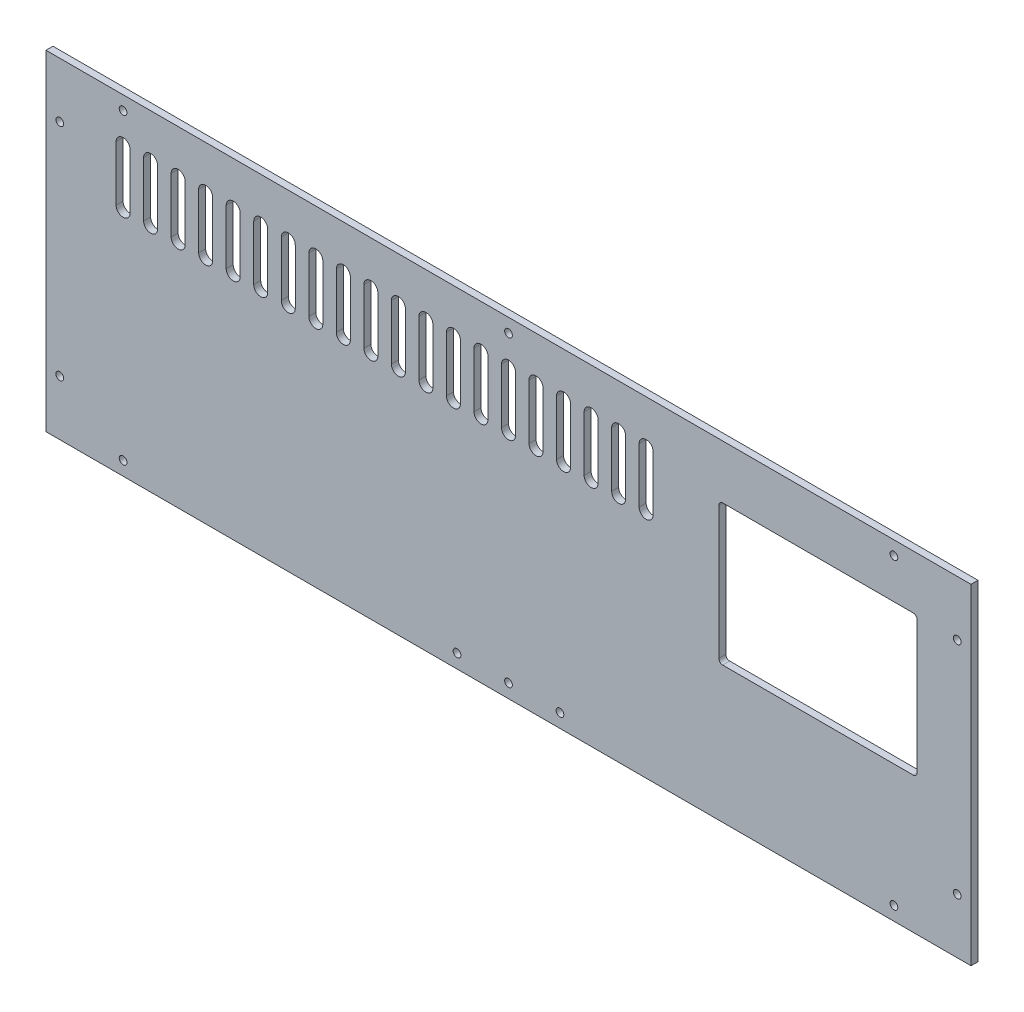
SolidWorks part; units mm, degrees
material "Acrylic (Medium-high impact)"
ref_plane "Front Plane" through (0, 0, 0) normal (0, 0, 1) x (1, 0, 0)
ref_plane "Top Plane" through (0, 0, 0) normal (0, 1, 0) x (1, 0, 0)
ref_plane "Right Plane" through (0, 0, 0) normal (1, 0, 0) x (0, 0, -1)
sketch "Sketch2" plane through (0, 0, 0) normal (0, 0, 1) x (1, 0, 0)
  line L1 (0, 0) -> (840, 0)
  line L2 (0, 0) -> (0, 300)
  line L3 (0, 300) -> (840, 300)
  line L4 (840, 0) -> (840, 300)
  dimension "D1" = 300
  dimension "D2" = 840
extrude "Boss-Extrude1" add sketch "Sketch2" along normal blind 6.35
sketch "Sketch3" plane through (0, 0, 6.35) normal (0, 0, 1) x (1, 0, 0)
  line L0 (420, 300) -> (420, 235) construction
  line L1 (840, 300) -> (0, 300) construction
  line L2 (420, 210) -> (420, 260) construction
  line L3 (413.65, 210) -> (413.65, 260)
  line L4 (426.35, 210) -> (426.35, 260)
  line L13 (451.35, 210) -> (451.35, 260)
  line L22 (438.65, 210) -> (438.65, 260)
  line L31 (445, 210) -> (445, 260) construction
  line L40 (476.35, 210) -> (476.35, 260)
  line L43 (463.65, 210) -> (463.65, 260)
  line L46 (470, 210) -> (470, 260) construction
  line L49 (501.35, 210) -> (501.35, 260)
  line L50 (488.65, 210) -> (488.65, 260)
  line L51 (401.35, 210) -> (401.35, 260)
  line L52 (388.65, 210) -> (388.65, 260)
  line L53 (395, 210) -> (395, 260) construction
  line L54 (376.35, 210) -> (376.35, 260)
  line L55 (363.65, 210) -> (363.65, 260)
  line L56 (370, 210) -> (370, 260) construction
  line L57 (351.35, 210) -> (351.35, 260)
  line L58 (338.65, 210) -> (338.65, 260)
  line L59 (345, 210) -> (345, 260) construction
  line L60 (326.35, 210) -> (326.35, 260)
  line L61 (313.65, 210) -> (313.65, 260)
  line L62 (320, 210) -> (320, 260) construction
  line L63 (301.35, 210) -> (301.35, 260)
  line L64 (288.65, 210) -> (288.65, 260)
  line L65 (295, 210) -> (295, 260) construction
  line L66 (276.35, 210) -> (276.35, 260)
  line L67 (263.65, 210) -> (263.65, 260)
  line L68 (270, 210) -> (270, 260) construction
  line L69 (251.35, 210) -> (251.35, 260)
  line L70 (238.65, 210) -> (238.65, 260)
  line L71 (245, 210) -> (245, 260) construction
  line L72 (226.35, 210) -> (226.35, 260)
  line L73 (213.65, 210) -> (213.65, 260)
  line L74 (220, 210) -> (220, 260) construction
  line L75 (201.35, 210) -> (201.35, 260)
  line L76 (188.65, 210) -> (188.65, 260)
  line L77 (195, 210) -> (195, 260) construction
  line L78 (176.35, 210) -> (176.35, 260)
  line L79 (163.65, 210) -> (163.65, 260)
  line L80 (170, 210) -> (170, 260) construction
  line L81 (151.35, 210) -> (151.35, 260)
  line L82 (138.65, 210) -> (138.65, 260)
  line L83 (145, 210) -> (145, 260) construction
  line L84 (126.35, 210) -> (126.35, 260)
  line L85 (113.65, 210) -> (113.65, 260)
  line L86 (120, 210) -> (120, 260) construction
  line L87 (101.35, 210) -> (101.35, 260)
  line L88 (88.65, 210) -> (88.65, 260)
  line L89 (95, 210) -> (95, 260) construction
  line L90 (76.35, 210) -> (76.35, 260)
  line L91 (63.65, 210) -> (63.65, 260)
  line L92 (70, 210) -> (70, 260) construction
  line L96 (426.35, 210) -> (401.35, 210) construction
  line L97 (495, 210) -> (495, 260) construction
  line L98 (526.35, 210) -> (526.35, 260)
  line L99 (513.65, 210) -> (513.65, 260)
  line L100 (520, 210) -> (520, 260) construction
  line L101 (551.35, 210) -> (551.35, 260)
  line L102 (538.65, 210) -> (538.65, 260)
  line L103 (545, 210) -> (545, 260) construction
  line L107 (426.35, 210) -> (451.35, 210) construction
  line L108 (38.65, 210) -> (38.65, 260) [skipped]
  line L109 (51.35, 210) -> (51.35, 260) [skipped]
  line L110 (563.65, 210) -> (563.65, 260) [skipped]
  line L111 (576.35, 210) -> (576.35, 260) [skipped]
  arc A0 (413.65, 210) -> (426.35, 210) centre (420, 210) ccw
  arc A1 (426.35, 260) -> (413.65, 260) centre (420, 260) ccw
  arc A32 (388.65, 210) -> (401.35, 210) centre (395, 210) ccw
  arc A33 (401.35, 260) -> (388.65, 260) centre (395, 260) ccw
  arc A34 (363.65, 210) -> (376.35, 210) centre (370, 210) ccw
  arc A35 (376.35, 260) -> (363.65, 260) centre (370, 260) ccw
  arc A36 (338.65, 210) -> (351.35, 210) centre (345, 210) ccw
  arc A37 (351.35, 260) -> (338.65, 260) centre (345, 260) ccw
  arc A38 (313.65, 210) -> (326.35, 210) centre (320, 210) ccw
  arc A39 (326.35, 260) -> (313.65, 260) centre (320, 260) ccw
  arc A40 (288.65, 210) -> (301.35, 210) centre (295, 210) ccw
  arc A41 (301.35, 260) -> (288.65, 260) centre (295, 260) ccw
  arc A42 (263.65, 210) -> (276.35, 210) centre (270, 210) ccw
  arc A43 (276.35, 260) -> (263.65, 260) centre (270, 260) ccw
  arc A44 (238.65, 210) -> (251.35, 210) centre (245, 210) ccw
  arc A45 (251.35, 260) -> (238.65, 260) centre (245, 260) ccw
  arc A46 (213.65, 210) -> (226.35, 210) centre (220, 210) ccw
  arc A47 (226.35, 260) -> (213.65, 260) centre (220, 260) ccw
  arc A48 (188.65, 210) -> (201.35, 210) centre (195, 210) ccw
  arc A49 (201.35, 260) -> (188.65, 260) centre (195, 260) ccw
  arc A50 (163.65, 210) -> (176.35, 210) centre (170, 210) ccw
  arc A51 (176.35, 260) -> (163.65, 260) centre (170, 260) ccw
  arc A52 (138.65, 210) -> (151.35, 210) centre (145, 210) ccw
  arc A53 (151.35, 260) -> (138.65, 260) centre (145, 260) ccw
  arc A54 (113.65, 210) -> (126.35, 210) centre (120, 210) ccw
  arc A55 (126.35, 260) -> (113.65, 260) centre (120, 260) ccw
  arc A56 (88.65, 210) -> (101.35, 210) centre (95, 210) ccw
  arc A57 (101.35, 260) -> (88.65, 260) centre (95, 260) ccw
  arc A58 (63.65, 210) -> (76.35, 210) centre (70, 210) ccw
  arc A59 (76.35, 260) -> (63.65, 260) centre (70, 260) ccw
  arc A70 (438.65, 210) -> (451.35, 210) centre (445, 210) ccw
  arc A71 (451.35, 260) -> (438.65, 260) centre (445, 260) ccw
  arc A72 (463.65, 210) -> (476.35, 210) centre (470, 210) ccw
  arc A73 (476.35, 260) -> (463.65, 260) centre (470, 260) ccw
  arc A74 (488.65, 210) -> (501.35, 210) centre (495, 210) ccw
  arc A75 (501.35, 260) -> (488.65, 260) centre (495, 260) ccw
  arc A76 (513.65, 210) -> (526.35, 210) centre (520, 210) ccw
  arc A77 (526.35, 260) -> (513.65, 260) centre (520, 260) ccw
  arc A78 (538.65, 210) -> (551.35, 210) centre (545, 210) ccw
  arc A79 (551.35, 260) -> (538.65, 260) centre (545, 260) ccw
  arc A82 (38.65, 210) -> (51.35, 210) centre (45, 210) ccw [skipped]
  arc A83 (51.35, 260) -> (38.65, 260) centre (45, 260) ccw [skipped]
  arc A84 (563.65, 210) -> (576.35, 210) centre (570, 210) ccw [skipped]
  arc A85 (576.35, 260) -> (563.65, 260) centre (570, 260) ccw [skipped]
  point P6 (420, 235)
  point P15 (445, 235)
  point P22 (470, 235)
  point P29 (495, 235)
  point P36 (520, 235)
  point P43 (545, 235)
  point P121 (395, 235)
  point P128 (370, 235)
  point P135 (345, 235)
  point P142 (320, 235)
  point P149 (295, 235)
  point P156 (270, 235)
  point P163 (245, 235)
  point P170 (220, 235)
  point P177 (195, 235)
  point P184 (170, 235)
  point P191 (145, 235)
  point P198 (120, 235)
  point P205 (95, 235)
  point P212 (70, 235)
  dimension "D3" = 6.35
  dimension "D1" = 65
  dimension "D2" = 25
  dimension "D5" = 25
  dimension "D7" = 25
  dimension "D6" = 16
  dimension "D4" = 7
extrude "Cut-Extrude1" cut sketch "Sketch3" against normal up to surface (6.35 mm away) up to face at (420, 150, 0)
ref_plane "Plane1" through (0, 150, 0) normal (0, 1, 0) x (1, 0, 0)
ref_plane "Plane2" through (420, 0, 0) normal (1, 0, 0) x (0, 0, -1)
sketch "Sketch4" plane through (0, 0, 6.35) normal (0, 0, 1) x (1, 0, 0)
  line L0 (420, 300) -> (420, 287.5) construction
  line L1 (840, 300) -> (0, 300) construction
  line L2 (420, 287.5) -> (770, 287.5) construction
  line L3 (420, 287.5) -> (70, 287.5) construction
  line L4 (0, 150) -> (12.5, 150) construction
  line L5 (0, 300) -> (0, 0) construction
  line L6 (12.5, 150) -> (12.5, 250) construction
  line L7 (12.5, 150) -> (12.5, 50) construction
  line L8 (420, -3.4925) -> (420, 3.4925) construction
  line L9 (3.4925, 150) -> (-3.4925, 150) construction
  line L10 (373.25, 12.5) -> (466.75, 12.5) construction
  circle A0 centre (420, 287.5) radius 3.5
  circle A1 centre (770, 287.5) radius 3.5
  circle A2 centre (70, 287.5) radius 3.5
  circle A3 centre (12.5, 250) radius 3.5
  circle A4 centre (12.5, 50) radius 3.5
  circle A5 centre (827.5, 50) radius 3.5
  circle A6 centre (827.5, 250) radius 3.5
  circle A7 centre (770, 12.5) radius 3.5
  circle A8 centre (420, 12.5) radius 3.5
  circle A9 centre (70, 12.5) radius 3.5
  circle A10 centre (373.25, 12.5) radius 3.5
  circle A11 centre (466.75, 12.5) radius 3.5
  point P33 (420, 12.5)
  dimension "D2" = 7
  dimension "D1" = 12.5
  dimension "D3" = 350
  dimension "D4" = 100
  dimension "D5" = 93.5
extrude "Cut-Extrude2" cut sketch "Sketch4" against normal through all
sketch "Sketch5" plane through (0, 0, 6.35) normal (0, 0, 1) x (1, 0, 0)
  line L0 (840, 300) -> (806, 300) construction
  line L1 (840, 300) -> (0, 300) construction
  line L2 (806, 300) -> (806, 266) construction
  line L3 (806, 266) -> (701, 266) construction
  line L4 (701, 266) -> (596, 266) construction
  line L5 (806, 266) -> (806, 109) construction
  line L6 (806, 109) -> (701, 109) construction
  line L7 (701, 109) -> (596, 109) construction
  line L8 (701, 266) -> (701, 251.25) construction
  line L9 (611, 251.25) -> (791, 251.25)
  line L10 (611, 251.25) -> (611, 123.75)
  line L11 (611, 123.75) -> (791, 123.75)
  line L12 (791, 251.25) -> (791, 123.75)
  line L13 (701, 123.75) -> (701, 109) construction
  dimension "D1" = 34
  dimension "D2" = 34
  dimension "D3" = 105
  dimension "D4" = 157
  dimension "D6" = 127.5
  dimension "D7" = 180
extrude "Cut-Extrude3" cut sketch "Sketch5" against normal through all
fillet "Fillet1" radius 3.5 4 edges at (791, 123.75, 3.175) (611, 123.75, 3.175) (791, 251.25, 3.175) (611, 251.25, 3.175)
